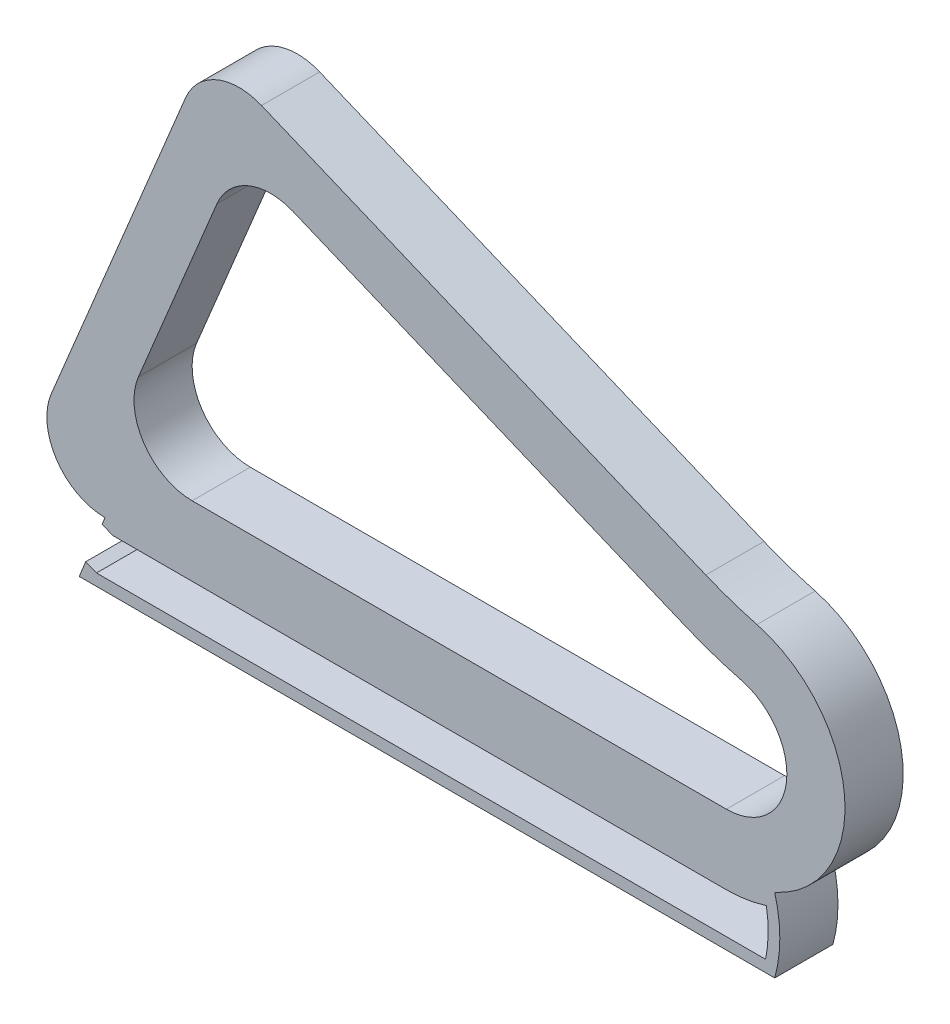
SolidWorks part; units mm, degrees
ref_plane "Front Plane" through (0, 0, 0) normal (0, 0, 1) x (1, 0, 0)
ref_plane "Top Plane" through (0, 0, 0) normal (0, 1, 0) x (1, 0, 0)
ref_plane "Right Plane" through (0, 0, 0) normal (1, 0, 0) x (0, 0, -1)
sketch "Sketch1" plane through (0, 0, 0) normal (0, 0, 1) x (1, 0, 0)
  line L0 (-61.1046, -23.8818) -> (45.7316, -23.8818)
  line L1 (45.7316, -3.0688) -> (-38.028, 31.7041)
  line L2 (-38.028, 31.7041) -> (-61.1046, -23.8818)
  line L3 (-76.0836, -33.8818) -> (45.7316, -33.8818)
  line L4 (48.0405, 6.8001) -> (-43.4295, 44.774)
  line L5 (-43.4295, 44.774) -> (-76.0836, -33.8818)
  arc A0 (45.7316, -23.8818) -> (45.7316, -3.0688) centre (45.7316, -13.4753) ccw
  arc A1 (45.7316, -33.8818) -> (48.0405, 6.8001) centre (45.7316, -13.4753) ccw
  point P0 (-92.1356, -41.4991)
  dimension "D1" = 10
extrude "Boss-Extrude3" add sketch "Sketch1" along normal blind 10
fillet "Fillet1" radius 10 1 edges at (-76.0836, -33.8818, 5)
fillet "Fillet2" radius 10 1 edges at (-61.1046, -23.8818, 5)
sketch "Sketch2" plane through (0, 0, 10) normal (0, 0, 1) x (1, 0, 0)
  line L0 (-61.1046, -33.8818) -> (-61.1046, -39.1547)
  line L1 (45.7316, -33.8818) -> (45.7316, -39.1547)
  line L2 (45.7316, -39.1547) -> (-61.1046, -39.1547)
  line L3 (-61.1046, -33.8818) -> (45.7316, -33.8818)
fillet "Fillet3" radius 10 2 edges at (-38.028, 31.7041, 5) (-43.4295, 44.774, 5)
fillet "Fillet4" radius 70 1 edges at (48.0405, 6.8001, 5)
fillet "Fillet5" radius 70 1 edges at (45.7316, -3.0688, 5)
sketch "Sketch3" plane through (0, 0, 10) normal (0, 0, 1) x (1, 0, 0)
  line L0 (-61.1046, -33.8818) -> (45.7316, -33.8818)
  line L1 (-61.1046, -33.8818) -> (-65.5383, -44.8619)
  line L3 (-65.5383, -44.8619) -> (41.2979, -44.8619)
  line L5 (41.2979, -44.8619) -> (54.0507, -44.8619)
  line L7 (-59.7553, -35.8818) -> (45.7316, -35.8818)
  line L8 (-59.7553, -35.8818) -> (-62.5738, -42.8619)
  line L9 (-62.5738, -42.8619) -> (41.2979, -42.8619)
  line L10 (41.2979, -42.8619) -> (52.4794, -42.8619)
  arc A0 (45.7316, -33.8818) -> (50.9926, 6.2413) centre (45.7316, -13.4753) ccw construction
  arc A1 (45.7316, -33.8818) -> (54.0507, -32.1091) centre (45.7316, -13.4753) ccw
  arc A2 (54.0507, -44.8619) -> (54.0507, -32.1091) centre (31.2662, -38.4855) ccw
  arc A3 (52.4794, -42.8619) -> (52.6103, -34.7998) centre (31.2662, -38.4855) ccw
  arc A4 (45.7316, -35.8818) -> (52.6103, -34.7998) centre (45.7316, -13.4753) ccw
  dimension "D1" = 2
extrude "Boss-Extrude5" add sketch "Sketch3" against normal blind 10
sketch "Sketch4" plane through (-38.9205, 15.7158, 0) normal (0.9273, -0.3744, 0) x (0, 0, -1)
  line L0 (-10, -55.6454) -> (-10, -63.173)
  line L1 (-10, -63.173) -> (0, -63.173)
  line L2 (0, -63.173) -> (0, -55.6454)
  line L3 (0, -55.6454) -> (-10, -55.6454)
extrude "Cut-Extrude1" cut sketch "Sketch4" against normal up to next
sketch "Sketch6" plane through (0, 0, 10) normal (0, 0, 1) x (1, 0, 0)
  line L0 (-55.3613, -10.0476) -> (-41.8622, 22.4684)
  line L1 (-28.7923, 27.8699) -> (48.3337, -3.3994)
  line L3 (-61.1046, -33.8818) -> (45.7316, -33.8818)
  line L4 (50.9926, 6.2413) -> (-34.1938, 40.9398)
  line L5 (-47.2637, 35.5383) -> (-70.3403, -20.0476)
  arc A1 (-41.8622, 22.4684) -> (-28.7923, 27.8699) centre (-32.6265, 18.6341) cw
  arc A2 (48.3337, -3.3994) -> (45.7316, -23.8818) centre (45.7316, -13.4753) cw
  arc A3 (45.7316, -33.8818) -> (50.9926, 6.2413) centre (45.7316, -13.4753) ccw
  arc A4 (-34.1938, 40.9398) -> (-47.2637, 35.5383) centre (-37.9916, 31.616) ccw
  arc A5 (-70.3403, -20.0476) -> (-61.1046, -33.8818) centre (-61.1046, -23.8818) ccw
sketch "Sketch7" plane through (0, -23.8818, 0) normal (0, 1, 0) x (1, 0, 0)
  line L0 (-46.1256, -10) -> (-46.1256, 0) construction
  line L1 (-46.1256, -5) -> (45.7316, -5) construction
  line L2 (45.7316, -10) -> (45.7316, 0) construction
